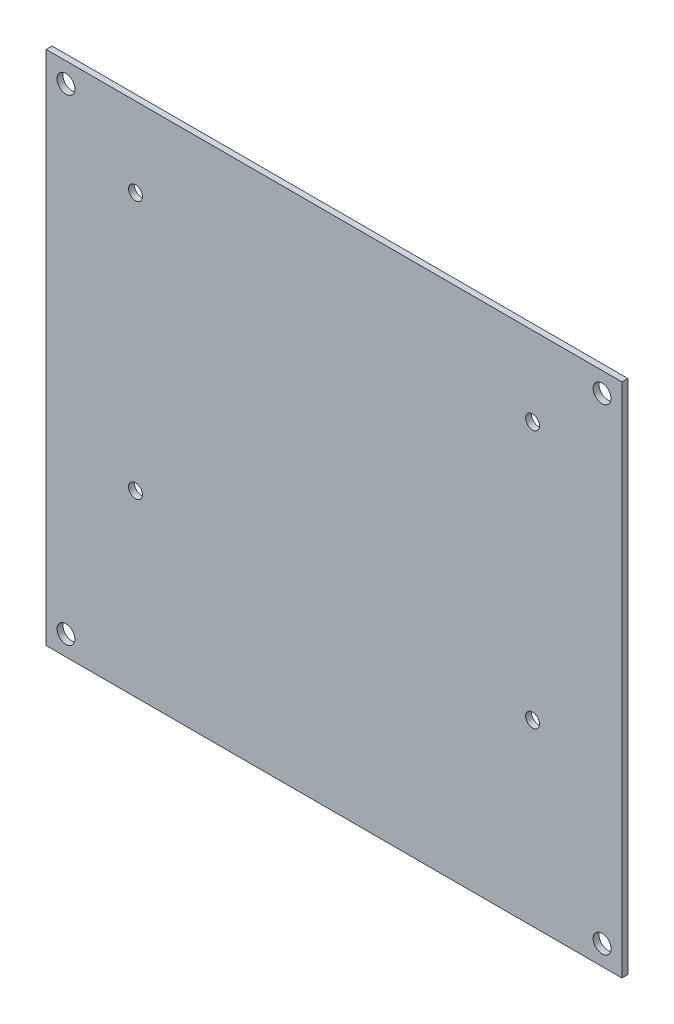
SolidWorks part; units mm, degrees
ref_plane "Спереди" through (0, 0, 0) normal (0, 0, 1) x (1, 0, 0)
ref_plane "Сверху" through (0, 0, 0) normal (0, 1, 0) x (1, 0, 0)
ref_plane "Справа" through (0, 0, 0) normal (1, 0, 0) x (0, 0, -1)
sketch "Эскиз1" plane through (0, 0, 0) normal (0, 0, 1) x (1, 0, 0)
  line L0 (0, 42.3611) -> (0, -41.9385) construction
  line L1 (-61.5264, 0) -> (36.4139, 0) construction
  line L2 (50, -20) -> (50, 45) construction
  line L3 (-72.5, -65) -> (72.5, -65)
  line L4 (-72.5, -65) -> (-72.5, 65)
  line L5 (-72.5, 65) -> (72.5, 65)
  line L6 (72.5, -65) -> (72.5, 65)
  circle A0 centre (-67.5, 60) radius 2.25
  circle A1 centre (-67.5, -60) radius 2.25
  circle A2 centre (67.5, -60) radius 2.25
  circle A3 centre (67.5, 60) radius 2.25
  circle A4 centre (-50, 45) radius 1.75
  circle A5 centre (-50, -20) radius 1.75
  circle A6 centre (50, 45) radius 1.75
  circle A7 centre (50, -20) radius 1.75
  dimension "D8" = 3.5
  dimension "D10" = 65
  dimension "D4" = 20
  dimension "D7" = 100
  dimension "D6" = 65
  dimension "D12" = 100
  dimension "D1" = 145
  dimension "D2" = 130
extrude "Вытянуть1" add sketch "Эскиз1" along normal blind 1.5
